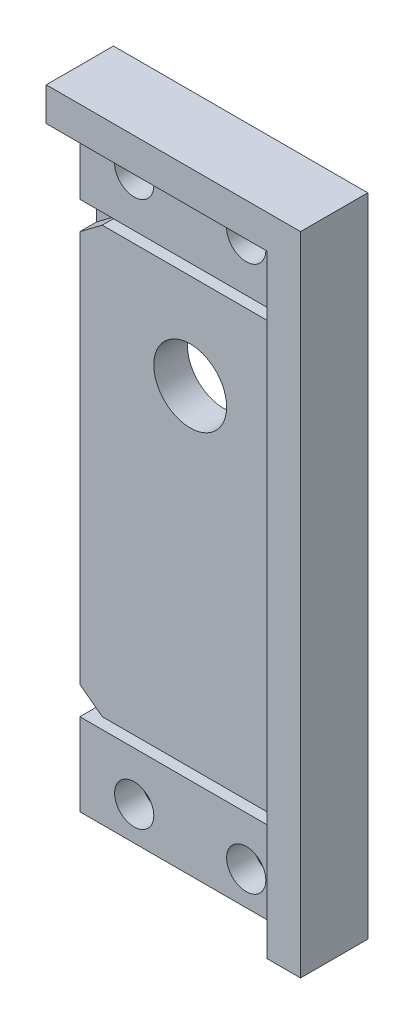
SolidWorks part; units mm, degrees
ref_plane "Alzado" through (0, 0, 0) normal (0, 0, 1) x (1, 0, 0)
ref_plane "Planta" through (0, 0, 0) normal (0, 1, 0) x (1, 0, 0)
ref_plane "Vista lateral" through (0, 0, 0) normal (1, 0, 0) x (0, 0, -1)
sketch "Croquis1" plane through (0, 0, 0) normal (0, 0, 1) x (1, 0, 0)
  line L0 (0, 0) -> (0, -27.35) construction
  line L1 (-9.85, 27.35) -> (9.85, 27.35)
  line L2 (-9.85, 27.35) -> (-9.85, -27.35)
  line L3 (-9.85, -27.35) -> (9.85, -27.35)
  line L4 (9.85, 27.35) -> (9.85, -27.35)
  line L5 (-9.85, 27.35) -> (9.85, -27.35) construction
  line L6 (-9.85, -27.35) -> (9.85, 27.35) construction
  line L7 (0, -27.35) -> (0, 27.35) construction
  line L8 (-9.85, -24.35) -> (9.85, -24.35) construction
  line L9 (-9.85, 0) -> (0, 0) construction
  line L10 (0, 0) -> (9.85, 0) construction
  line L11 (-5, -24.35) -> (-5, -18.8331) construction
  line L12 (-5, -18.8331) -> (0, -18.8331) construction
  line L13 (0, -18.8331) -> (5, -18.8331) construction
  line L14 (5, -18.8331) -> (5, -24.35) construction
  circle A0 centre (-5, -24.35) radius 1.75
  circle A1 centre (5, -24.35) radius 1.75
  circle A2 centre (5, 24.35) radius 1.75
  circle A3 centre (-5, 24.35) radius 1.75
  point P0 (0, 0)
  point P12 (0, -24.35)
  dimension "D4" = 3.5
  dimension "D5" = 3.5
  dimension "D1" = 19.7
  dimension "D2" = 54.7
  dimension "D3" = 3
  dimension "D6" = 10
extrude "Saliente-Extruir1" add sketch "Croquis1" along normal blind 3
chamfer "Chaflán1" distance 0.6 angle 45 4 edges at (-3.25, -24.35, 0) (6.75, -24.35, 0) (-6.75, 24.35, 0) (3.25, 24.35, 0)
sketch "Croquis2" plane through (0, 0, 3) normal (0, 0, 1) x (1, 0, 0)
  line L0 (9.85, -27.35) -> (9.85, 27.35) construction
  line L1 (-9.85, 20) -> (9.85, 20)
  line L2 (-9.85, 20) -> (-9.85, -20) construction
  line L3 (-9.85, -20) -> (9.85, -20)
  line L4 (9.85, 20) -> (9.85, -20) construction
  line L5 (-9.85, 20) -> (9.85, -20) construction
  line L6 (-9.85, -20) -> (9.85, 20) construction
  line L7 (-9.85, 20) -> (-9.85, 17.5)
  line L8 (-9.85, 17.5) -> (-7.85, 19)
  line L9 (-7.85, 19) -> (7.85, 19)
  line L10 (7.85, 19) -> (9.85, 17.5)
  line L11 (9.85, 17.5) -> (9.85, 20)
  line L12 (-9.85, 17.5) -> (9.85, 17.5) construction
  line L13 (0, 0) -> (9.85, 0) construction
  line L14 (9.85, -17.5) -> (9.85, -20)
  line L15 (7.85, -19) -> (9.85, -17.5)
  line L16 (-9.85, -20) -> (9.85, -20)
  line L17 (-7.85, -19) -> (7.85, -19)
  line L18 (-9.85, -17.5) -> (-7.85, -19)
  line L19 (-9.85, -20) -> (-9.85, -17.5)
  point P0 (0, 0)
  point P14 (8.0123, 18.8411)
  line M13 (9.85, -27.35) -> (9.85, 27.35)
  line M15 (-9.85, 27.35) -> (-9.85, -27.35)
  dimension "D1" = 40
  dimension "D2" = 1
  dimension "D3" = 2.5
  dimension "D4" = 2
extrude "Cortar-Extruir1" cut sketch "Croquis2" against normal blind 1.5 contours L9 L10 L1 L8 M13 M15 | L18 L3 L15 L17 M15 M13
sketch "Croquis3" plane through (0, 0, 3) normal (0, 0, 1) x (1, 0, 0)
  line L0 (0, 0) -> (0, 10.5) construction
  line L1 (-9.85, 20) -> (9.85, 20) construction
  circle A0 centre (0, 10.5) radius 3.25
  dimension "D1" = 6.5
  dimension "D2" = 9.5
extrude "Cortar-Extruir2" cut sketch "Croquis3" against normal through all
sketch "Croquis4" plane through (0, 0, 0) normal (0, 0, -1) x (-1, 0, 0)
  line L0 (-9.85, -27.35) -> (-12.85, -27.35)
  line L1 (-12.85, -27.35) -> (-12.85, 30.35)
  line L2 (-12.85, 30.35) -> (9.85, 30.35)
  line L3 (9.85, 30.35) -> (9.85, 27.35)
  line L4 (9.85, 27.35) -> (-9.85, 27.35)
  line L5 (-9.85, 27.35) -> (-9.85, -27.35)
  dimension "D1" = 3
extrude "Saliente-Extruir2" add sketch "Croquis4" against normal blind 6
